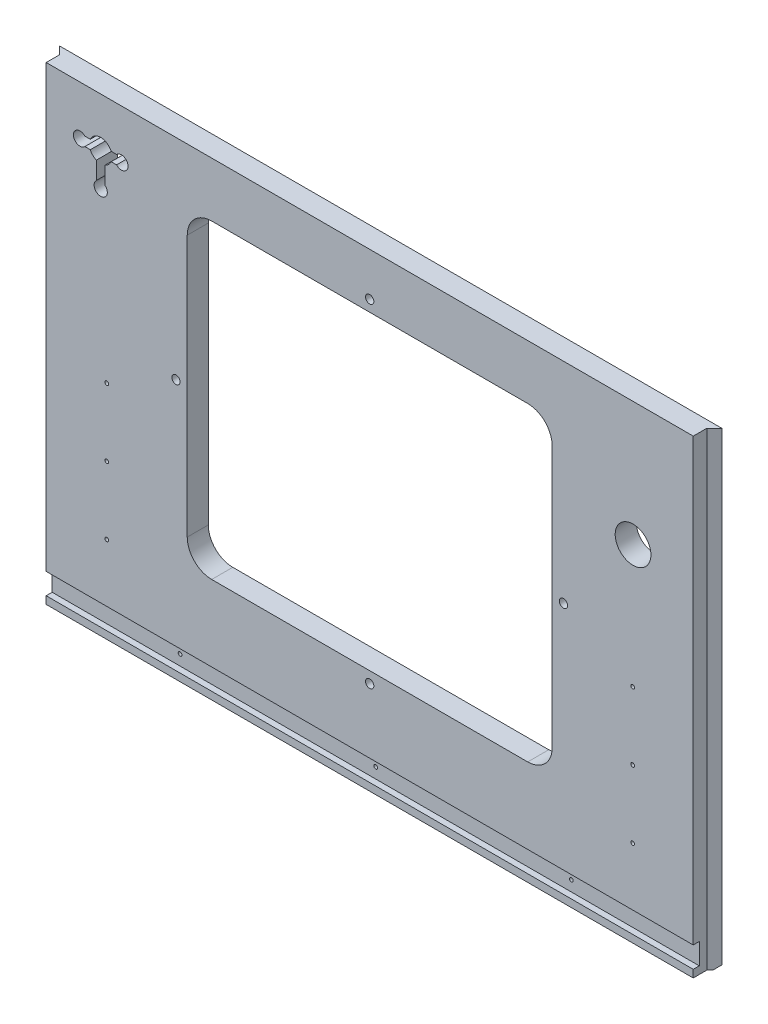
SolidWorks part; units mm, degrees
material "Pine"
ref_plane "Front Plane" through (0, 0, 0) normal (0, 0, 1) x (1, 0, 0)
ref_plane "Top Plane" through (0, 0, 0) normal (0, 1, 0) x (1, 0, 0)
ref_plane "Right Plane" through (0, 0, 0) normal (1, 0, 0) x (0, 0, -1)
sketch "Sketch1" plane through (0, 0, 0) normal (0, 0, 1) x (1, 0, 0)
  line L0 (8932.6508, -5243.5125) -> (10226.1458, -5243.5125)
  line L1 (9086.3208, -4722.0918) -> (10222.9708, -4853.7812)
  line L2 (8914.8708, -6342.0625) -> (10197.5708, -6342.0625)
  line L3 (8914.8708, -5808.6625) -> (10197.5708, -5808.6625)
  line L4 (8919.6333, -5253.0375) -> (10218.2083, -5253.0375)
  line L5 (9134.2633, -4656.1375) -> (9134.2633, -4638.3575)
  line L6 (9091.0833, -4638.3575) -> (9134.2633, -4638.3575)
  line L7 (9091.0833, -4567.2375) -> (9091.0833, -4638.3575)
  line L8 (9134.2633, -4656.1375) -> (9581.3033, -4656.1375)
  line L9 (9091.0833, -4567.2375) -> (9624.4833, -4567.2375)
  line L10 (9581.3033, -4656.1375) -> (9581.3033, -4638.3575)
  line L11 (9581.3033, -4638.3575) -> (9624.4833, -4638.3575)
  line L12 (9624.4833, -4567.2375) -> (9624.4833, -4638.3575)
  line L13 (8932.6508, -5225.7325) -> (9344.9775, -5225.7325)
  line L14 (8932.6508, -5256.2125) -> (8932.6508, -5243.5125)
  line L15 (8911.6958, -5256.2125) -> (8932.6508, -5256.2125)
  line L16 (8914.8708, -4722.0918) -> (9086.3208, -4722.0918)
  line L17 (8911.6958, -4715.5913) -> (8932.6508, -4715.5913)
  line L18 (8914.8708, -6342.0625) -> (8914.8708, -5808.6625)
  line L19 (12082.9917, -4722.0918) -> (10946.3417, -4853.7812)
  line L20 (12236.6617, -5243.5125) -> (10943.1667, -5243.5125)
  line L21 (10951.1042, -5253.0375) -> (12249.6792, -5253.0375)
  line L22 (10838.3917, -5656.2625) -> (11308.2917, -5656.2625)
  line L23 (10838.3917, -5719.7625) -> (11308.2917, -5719.7625)
  line L24 (10838.3917, -5742.5368) -> (11308.2917, -5742.5368)
  line L25 (10806.6417, -6342.0625) -> (11340.0417, -6342.0625)
  line L26 (10803.4667, -6335.7125) -> (11343.2167, -6335.7125)
  line L27 (10803.4667, -6317.9325) -> (11343.2167, -6317.9325)
  line L28 (10943.1667, -5225.7325) -> (11376.4483, -5225.7325)
  line L29 (11506.7292, -4754.5625) -> (10806.6417, -4827.5875)
  line L30 (11506.7292, -4567.2375) -> (11506.7292, -4754.5625)
  line L31 (10806.6417, -4567.2375) -> (10806.6417, -4827.5875)
  line L32 (10806.6417, -4567.2375) -> (11506.7292, -4567.2375)
  line L33 (10235.6708, -6329.3625) -> (10245.1958, -6329.3625)
  line L34 (10245.1958, -6329.3625) -> (10254.7208, -6278.5625)
  line L35 (10302.3458, -6329.3625) -> (10311.8708, -6278.5625)
  line L36 (10302.3458, -6329.3625) -> (10292.8208, -6329.3625)
  line L37 (10245.1958, -5821.3625) -> (10254.7208, -5872.1625)
  line L38 (10235.6708, -5821.3625) -> (10245.1958, -5821.3625)
  line L39 (10292.8208, -5821.3625) -> (10302.3458, -5821.3625)
  line L40 (10302.3458, -5821.3625) -> (10311.8708, -5872.1625)
  line L41 (10235.6708, -5821.3625) -> (10235.6708, -6329.3625)
  line L42 (10254.7208, -5872.1625) -> (10254.7208, -6278.5625)
  line L43 (10311.8708, -5872.1625) -> (10311.8708, -6278.5625)
  line L44 (10292.8208, -5821.3625) -> (10292.8208, -6329.3625)
  line L45 (8932.6508, -5225.7325) -> (8932.6508, -4715.5913)
  line L46 (8911.6958, -4715.5913) -> (8911.6958, -5256.2125)
  line L47 (8914.8708, -5248.275) -> (8914.8708, -4722.0918)
  line L48 (8919.6333, -5253.0375) -> (8914.8708, -5248.275)
  line L49 (8914.8708, -5145.0875) -> (8937.426, -5145.0875)
  line L50 (8914.8708, -5202.2375) -> (8937.426, -5202.2375)
  line L51 (10838.3917, -5656.2625) -> (10838.3917, -5719.7625)
  line L52 (10832.0417, -5736.1868) -> (10856.1717, -5736.1868)
  line L53 (10806.6417, -6342.0625) -> (10806.6417, -5818.7368)
  line L54 (10832.0417, -5649.9125) -> (10856.1717, -5649.9125)
  line L55 (10832.0417, -5726.1125) -> (10856.1717, -5726.1125)
  line L56 (10806.6417, -5818.7368) -> (10833.9015, -5818.7368)
  line L57 (10832.0417, -5806.0442) -> (10851.6815, -5806.0442)
  line L58 (10856.1717, -5801.5541) -> (10856.1717, -5736.1868)
  line L59 (10838.3917, -5814.2467) -> (10838.3917, -5742.5368)
  line L60 (10832.0417, -5806.0442) -> (10832.0417, -5736.1868)
  line L61 (10803.4667, -6317.9325) -> (10803.4667, -6335.7125)
  line L62 (10197.5708, -5808.6625) -> (10197.5708, -6342.0625)
  line L63 (9762.3842, -6348.4125) -> (9762.3842, -5802.3125)
  line L64 (9780.1642, -6348.4125) -> (9762.3842, -6348.4125)
  line L65 (9780.1642, -5802.3125) -> (9780.1642, -6348.4125)
  line L66 (9762.3842, -5802.3125) -> (9780.1642, -5802.3125)
  line L67 (9332.2775, -6348.4125) -> (9332.2775, -5802.3125)
  line L68 (9332.2775, -6348.4125) -> (9350.0575, -6348.4125)
  line L69 (9350.0575, -5802.3125) -> (9350.0575, -6348.4125)
  line L70 (9332.2775, -5802.3125) -> (9350.0575, -5802.3125)
  line L71 (9993.8374, -6061.075) -> (9993.8374, -6045.2418)
  line L72 (9998.5999, -6065.8375) -> (10014.4331, -6065.8375)
  line L73 (9998.5999, -6084.8875) -> (10014.4331, -6084.8875)
  line L74 (9993.8374, -6105.4832) -> (9993.8374, -6089.65)
  line L75 (9974.7874, -6105.4832) -> (9974.7874, -6089.65)
  line L76 (9954.1917, -6084.8875) -> (9970.0249, -6084.8875)
  line L77 (9974.7874, -6061.075) -> (9974.7874, -6045.2418)
  line L78 (9954.1917, -6065.8375) -> (9970.0249, -6065.8375)
  line L79 (10793.9417, -6237.2875) -> (10816.4969, -6237.2875)
  line L80 (10793.9417, -6294.4375) -> (10816.4969, -6294.4375)
  line L81 (10856.1717, -5649.9125) -> (10856.1717, -5726.1125)
  line L82 (10832.0417, -5726.1125) -> (10832.0417, -5649.9125)
  line L83 (10226.1458, -5225.7325) -> (10226.1458, -5243.5125)
  line L84 (10205.1908, -5257.8) -> (10205.1908, -4844.2499)
  line L85 (10230.9083, -4844.2499) -> (10230.9083, -5257.8)
  line L86 (10205.1908, -5257.8) -> (10230.9083, -5257.8)
  line L87 (10205.1908, -4844.2499) -> (10230.9083, -4844.2499)
  line L88 (10946.3417, -5176.8375) -> (10968.8969, -5176.8375)
  line L89 (9349.4676, -5141.9125) -> (9358.2674, -5141.9125)
  line L90 (10946.3417, -5119.6875) -> (10968.8969, -5119.6875)
  line L91 (9929.011, -4660.9635) -> (10066.0807, -4660.9635)
  line L92 (9929.011, -4678.7435) -> (10066.0807, -4678.7435)
  line L93 (10943.1667, -5225.7325) -> (10943.1667, -5243.5125)
  line L94 (10946.3417, -5248.275) -> (10951.1042, -5253.0375)
  line L95 (10946.3417, -5257.8063) -> (10946.3417, -4849.0188)
  line L96 (10964.1217, -5257.8) -> (10964.1217, -4844.2499)
  line L97 (10938.4042, -4844.2499) -> (10938.4042, -5257.8)
  line L98 (10938.4042, -5257.8) -> (10964.1217, -5257.8)
  line L99 (10964.1217, -4844.2499) -> (10938.4042, -4844.2499)
  line L100 (10344.8908, -4560.8875) -> (10369.0208, -4560.8875)
  line L101 (10344.8908, -4560.8875) -> (10369.0208, -4560.8875)
  line L102 (10800.2917, -4560.8875) -> (10824.4217, -4560.8875)
  line L103 (10200.4156, -5119.6875) -> (10222.9708, -5119.6875)
  line L104 (10200.4156, -5176.8375) -> (10222.9708, -5176.8375)
  line L105 (9344.9775, -5146.4026) -> (9344.9775, -5225.7325)
  line L106 (10344.8908, -4560.8875) -> (10344.8908, -4833.9375)
  line L107 (9792.8642, -5225.7325) -> (9792.8642, -5146.4026)
  line L108 (9362.7575, -5225.7325) -> (9775.0842, -5225.7325)
  line L109 (9680.3633, -4761.8396) -> (9680.3633, -4559.9604)
  line L110 (9656.2333, -4559.9604) -> (9680.3633, -4559.9604)
  line L111 (9656.2333, -4761.8396) -> (9680.3633, -4761.8396)
  line L112 (9656.2333, -4761.8396) -> (9656.2333, -4559.9604)
  line L113 (9779.5743, -5141.9125) -> (9788.374, -5141.9125)
  line L114 (10070.5708, -4665.4536) -> (10070.5708, -4674.2534)
  line L115 (9924.5208, -4674.2534) -> (9924.5208, -4665.4536)
  line L116 (12127.4417, -6188.3925) -> (12205.5015, -6188.3925)
  line L117 (12209.9917, -6170.6125) -> (12209.9917, -6183.9024)
  line L118 (9792.8642, -5225.7325) -> (10226.1458, -5225.7325)
  line L119 (9662.5833, -4754.5625) -> (10362.6708, -4827.5875)
  line L120 (9662.5833, -4567.2375) -> (9662.5833, -4754.5625)
  line L121 (10362.6708, -4567.2375) -> (10362.6708, -4827.5875)
  line L122 (9662.5833, -4567.2375) -> (10362.6708, -4567.2375)
  line L123 (10824.4217, -4833.9375) -> (10800.2917, -4833.9375)
  line L124 (10800.2917, -4833.9375) -> (10800.2917, -4560.8875)
  line L125 (10824.4217, -4560.8875) -> (10824.4217, -4833.9375)
  line L126 (10344.8908, -4833.9375) -> (10369.0208, -4833.9375)
  line L127 (10369.0208, -4833.9375) -> (10369.0208, -4560.8875)
  line L128 (10222.9708, -5248.275) -> (10218.2083, -5253.0375)
  line L129 (10222.9708, -5257.8063) -> (10222.9708, -4849.0188)
  line L130 (11734.6544, -5701.375) -> (11739.2301, -5701.375)
  line L131 (9362.7575, -5225.7325) -> (9362.7575, -5146.4026)
  line L132 (9775.0842, -5146.4026) -> (9775.0842, -5225.7325)
  line L133 (11761.3864, -5701.375) -> (11756.8282, -5701.375)
  line L134 (11734.6544, -5693.755) -> (11739.2301, -5693.755)
  line L135 (11761.4039, -5693.755) -> (11756.8282, -5693.755)
  line L136 (11734.6544, -5701.375) -> (11739.2301, -5701.375)
  line L137 (11744.3462, -5721.3024) -> (11744.3462, -5706.4179)
  line L138 (11751.7122, -5721.3024) -> (11751.7122, -5706.4179)
  line L139 (11740.0917, -6170.6125) -> (11740.0917, -6183.9024)
  line L140 (11689.2917, -6188.3925) -> (11822.6417, -6188.3925)
  line L141 (11689.2917, -6348.4093) -> (11689.2917, -6164.2657)
  line L142 (11689.2917, -6164.2657) -> (11746.4417, -6164.2657)
  line L143 (11746.4417, -6164.2657) -> (11746.4417, -6188.3925)
  line L144 (11689.2917, -6164.2657) -> (11746.4417, -6164.2657)
  line L145 (11340.0417, -5818.7368) -> (11340.0417, -6342.0625)
  line L146 (11290.5117, -5726.1125) -> (11314.6417, -5726.1125)
  line L147 (11290.5117, -5649.9125) -> (11290.5117, -5726.1125)
  line L148 (11340.0417, -5818.7368) -> (11312.7818, -5818.7368)
  line L149 (11314.6417, -5806.0442) -> (11295.0018, -5806.0442)
  line L150 (11290.5117, -5801.5541) -> (11290.5117, -5736.1868)
  line L151 (11308.2917, -5814.2467) -> (11308.2917, -5742.5368)
  line L152 (11314.6417, -5806.0442) -> (11314.6417, -5736.1868)
  line L153 (11290.5117, -5736.1868) -> (11314.6417, -5736.1868)
  line L154 (11848.0417, -6267.1325) -> (11962.3417, -6267.1325)
  line L155 (11962.3417, -6267.1325) -> (11962.3417, -6203.6325)
  line L156 (11343.2167, -6317.9325) -> (11343.2167, -6335.7125)
  line L157 (11365.4417, -5656.2625) -> (11365.4417, -5719.7625)
  line L158 (11365.4417, -5656.2625) -> (11479.7417, -5656.2625)
  line L159 (11778.1917, -6071.3937) -> (11802.3217, -6071.3937)
  line L160 (11314.6417, -5726.1125) -> (11314.6417, -5649.9125)
  line L161 (11314.6417, -5649.9125) -> (11290.5117, -5649.9125)
  line L162 (11308.2917, -5719.7625) -> (11308.2917, -5656.2625)
  line L163 (11689.2917, -6348.4093) -> (11713.4217, -6348.4093)
  line L164 (12203.6417, -6164.2657) -> (12260.7917, -6164.2657)
  line L165 (11713.4217, -6348.4093) -> (11713.4217, -6164.2657)
  line L166 (11695.6417, -6342.0625) -> (11695.6417, -6170.6125)
  line L167 (11695.6417, -6048.5337) -> (11699.4517, -6052.3437)
  line L168 (11822.6417, -6292.5325) -> (11822.6417, -6188.3925)
  line L169 (11695.6417, -6342.0625) -> (11695.6417, -6170.6125)
  line L170 (11848.0417, -6203.6325) -> (11962.3417, -6203.6325)
  line L171 (11848.0417, -6203.6325) -> (11848.0417, -6267.1325)
  line L172 (11987.7417, -6267.1325) -> (11987.7417, -6203.6325)
  line L173 (11784.5417, -6077.7437) -> (11784.5417, -6141.2438)
  line L174 (11517.8417, -5656.2625) -> (11632.1417, -5656.2625)
  line L175 (11632.1417, -5656.2625) -> (11632.1417, -5719.7625)
  line L176 (11632.1417, -5719.7625) -> (11517.8417, -5719.7625)
  line L177 (11517.8417, -5719.7625) -> (11517.8417, -5656.2625)
  line L178 (11692.4667, -6028.2137) -> (11692.4667, -6045.9937)
  line L179 (11695.6417, -5979.3188) -> (11718.1969, -5979.3188)
  line L180 (11695.6417, -5922.1687) -> (11718.1969, -5922.1687)
  line L181 (11821.0415, -5722.9375) -> (11821.0415, -5943.6)
  line L182 (11687.7042, -5651.5) -> (11701.9917, -5651.5)
  line L183 (11687.7042, -5651.5) -> (11687.7042, -6055.5251)
  line L184 (11687.7042, -6055.5251) -> (11701.9917, -6055.5251)
  line L185 (11701.9917, -6055.5251) -> (11701.9917, -5651.5)
  line L186 (11695.6417, -6055.2013) -> (11695.6417, -5649.595)
  line L187 (11695.6417, -5656.2625) -> (11695.6417, -6048.5337)
  line L188 (11695.6417, -6170.6125) -> (11740.0917, -6170.6125)
  line L189 (12203.6417, -6164.2657) -> (12203.6417, -6188.3925)
  line L190 (12254.4417, -6342.0625) -> (12254.4417, -6170.6125)
  line L191 (12129.0419, -5943.6) -> (12129.0419, -5722.9375)
  line L192 (12254.4417, -6048.5337) -> (12250.6317, -6052.3437)
  line L193 (12257.6167, -6045.9937) -> (12257.6167, -6028.2137)
  line L194 (12248.0917, -5651.5) -> (12262.3792, -5651.5)
  line L195 (12262.3792, -5651.5) -> (12262.3792, -6055.5251)
  line L196 (12262.3792, -6055.5251) -> (12248.0917, -6055.5251)
  line L197 (12248.0917, -6055.5251) -> (12248.0917, -5651.5)
  line L198 (12254.4417, -6141.2438) -> (12254.4417, -6077.7437)
  line L199 (12236.6617, -6164.2657) -> (12260.7917, -6164.2657)
  line L200 (12102.0417, -6267.1325) -> (11987.7417, -6267.1325)
  line L201 (11330.1865, -6237.2875) -> (11352.7417, -6237.2875)
  line L202 (11330.1865, -6294.4375) -> (11352.7417, -6294.4375)
  line L203 (11474.6617, -5851.8425) -> (11492.4417, -5851.8425)
  line L204 (11474.6617, -5808.6625) -> (11474.6617, -5851.8425)
  line L205 (11403.5417, -5808.6625) -> (11474.6617, -5808.6625)
  line L206 (11492.4417, -5851.8425) -> (11492.4417, -6298.8825)
  line L207 (11403.5417, -6342.0625) -> (11403.5417, -5808.6625)
  line L208 (11474.6617, -6298.8825) -> (11492.4417, -6298.8825)
  line L209 (11474.6617, -6342.0625) -> (11474.6617, -6298.8825)
  line L210 (11403.5417, -6342.0625) -> (11474.6617, -6342.0625)
  line L211 (11619.4417, -5851.8425) -> (11601.6617, -5851.8425)
  line L212 (11601.6617, -5808.6625) -> (11601.6617, -5851.8425)
  line L213 (11530.5417, -5808.6625) -> (11601.6617, -5808.6625)
  line L214 (11619.4417, -5851.8425) -> (11619.4417, -6298.8825)
  line L215 (11530.5417, -6342.0625) -> (11530.5417, -5808.6625)
  line L216 (11619.4417, -6298.8825) -> (11601.6617, -6298.8825)
  line L217 (11601.6617, -6342.0625) -> (11601.6617, -6298.8825)
  line L218 (11530.5417, -6342.0625) -> (11601.6617, -6342.0625)
  line L219 (11479.7417, -5719.7625) -> (11479.7417, -5656.2625)
  line L220 (11365.4417, -5719.7625) -> (11479.7417, -5719.7625)
  line L221 (11778.1917, -6147.5937) -> (11802.3217, -6147.5937)
  line L222 (11802.3217, -6071.3937) -> (11802.3217, -6147.5937)
  line L223 (11778.1917, -6147.5937) -> (11778.1917, -6071.3937)
  line L224 (12254.4417, -5922.1687) -> (12231.8865, -5922.1687)
  line L225 (12254.4417, -5979.3188) -> (12231.8865, -5979.3188)
  line L226 (12254.4417, -6055.2013) -> (12254.4417, -5649.595)
  line L227 (12254.4417, -6048.5337) -> (12254.4417, -5656.2625)
  line L228 (11841.6917, -5702.2873) -> (12108.3917, -5702.2873)
  line L229 (11822.6417, -6292.5325) -> (12127.4417, -6292.5325)
  line L230 (12127.4417, -6292.5325) -> (12127.4417, -6188.3925)
  line L231 (12254.4417, -6170.6125) -> (12209.9917, -6170.6125)
  line L232 (11695.6417, -6342.0625) -> (12254.4417, -6342.0625)
  line L233 (12236.6617, -6348.4093) -> (12260.7917, -6348.4093)
  line L234 (12260.7917, -6348.4093) -> (12260.7917, -6164.2657)
  line L235 (12236.6617, -6348.4093) -> (12236.6617, -6164.2657)
  line L236 (12102.0417, -6203.6325) -> (12102.0417, -6267.1325)
  line L237 (11987.7417, -6203.6325) -> (12102.0417, -6203.6325)
  line L238 (12236.6617, -6147.5937) -> (12236.6617, -6071.3937)
  line L239 (12203.6417, -6188.3925) -> (12260.7917, -6188.3925)
  line L240 (11098.7417, -4665.4536) -> (11098.7417, -4674.2534)
  line L241 (11394.2283, -5146.4026) -> (11394.2283, -5225.7325)
  line L242 (11376.4483, -5225.7325) -> (11376.4483, -5146.4026)
  line L243 (11394.2283, -5225.7325) -> (11806.555, -5225.7325)
  line L244 (11841.6917, -5964.2502) -> (12108.3917, -5964.2502)
  line L245 (12236.6617, -6147.5937) -> (12260.7917, -6147.5937)
  line L246 (12236.6617, -5256.2125) -> (12236.6617, -5243.5125)
  line L247 (12260.7917, -6147.5937) -> (12260.7917, -6071.3937)
  line L248 (12260.7917, -6071.3937) -> (12236.6617, -6071.3937)
  line L249 (12254.4417, -6077.7437) -> (11784.5417, -6077.7437)
  line L250 (11784.5417, -6141.2438) -> (12254.4417, -6141.2438)
  line L252 (12254.4417, -5656.2625) -> (11695.6417, -5656.2625)
  line L253 (11699.4517, -6052.3437) -> (12250.6317, -6052.3437)
  line L254 (11692.4667, -6045.9937) -> (12257.6167, -6045.9937)
  line L255 (11692.4667, -6028.2137) -> (12257.6167, -6028.2137)
  line L256 (11824.335, -5146.4026) -> (11824.335, -5225.7325)
  line L257 (11811.0451, -5141.9125) -> (11819.8449, -5141.9125)
  line L258 (11244.7917, -4674.2534) -> (11244.7917, -4665.4536)
  line L259 (11806.555, -5225.7325) -> (11806.555, -5146.4026)
  line L260 (11488.9492, -4761.8396) -> (11488.9492, -4559.9604)
  line L261 (11488.9492, -4559.9604) -> (11513.0792, -4559.9604)
  line L262 (11488.9492, -4761.8396) -> (11513.0792, -4761.8396)
  line L263 (11513.0792, -4761.8396) -> (11513.0792, -4559.9604)
  line L264 (11240.3015, -4660.9635) -> (11103.2318, -4660.9635)
  line L265 (11103.2318, -4678.7435) -> (11240.3015, -4678.7435)
  line L266 (12236.6617, -5225.7325) -> (12236.6617, -4715.5913)
  line L267 (12257.6167, -4715.5913) -> (12257.6167, -5256.2125)
  line L268 (12254.4417, -5248.275) -> (12254.4417, -4722.0918)
  line L269 (12236.6617, -5225.7325) -> (11824.335, -5225.7325)
  line L270 (12035.0492, -4656.1375) -> (12035.0492, -4638.3575)
  line L271 (12078.2292, -4638.3575) -> (12035.0492, -4638.3575)
  line L272 (12078.2292, -4567.2375) -> (12078.2292, -4638.3575)
  line L273 (12035.0492, -4656.1375) -> (11588.0092, -4656.1375)
  line L274 (11544.8292, -4567.2375) -> (12078.2292, -4567.2375)
  line L275 (11588.0092, -4656.1375) -> (11588.0092, -4638.3575)
  line L276 (11544.8292, -4638.3575) -> (11588.0092, -4638.3575)
  line L277 (11544.8292, -4567.2375) -> (11544.8292, -4638.3575)
  line L278 (12249.6792, -5253.0375) -> (12254.4417, -5248.275)
  line L280 (12257.6167, -5256.2125) -> (12236.6617, -5256.2125)
  line L281 (12231.8865, -5145.0875) -> (12254.4417, -5145.0875)
  line L282 (12231.8865, -5202.2375) -> (12254.4417, -5202.2375)
  line L283 (12236.6617, -4715.5913) -> (12257.6167, -4715.5913)
  line L284 (12082.9917, -4722.0918) -> (12254.4417, -4722.0918)
  line L285 (11380.9385, -5141.9125) -> (11389.7382, -5141.9125)
  circle A0 centre (8923.7608, -4778.9042) radius 1.5875
  circle A1 centre (9062.6598, -4736.3765) radius 2.3685
  circle A2 centre (9051.3958, -6281.7375) radius 22.225
  circle A3 centre (9083.1458, -6249.9875) radius 1.5875
  circle A4 centre (9083.1458, -6313.4875) radius 1.5875
  circle A5 centre (9019.6458, -6249.9875) radius 1.5875
  circle A6 centre (9019.6458, -6313.4875) radius 1.5875
  circle A7 centre (8972.3383, -5202.2375) radius 1.5875
  circle A8 centre (8923.7608, -5015.9708) radius 1.5875
  circle A9 centre (8923.7608, -5134.5042) radius 1.5875
  circle A10 centre (9054.5708, -5234.6225) radius 1.5875
  circle A11 centre (8923.7608, -4897.4375) radius 1.5875
  circle A12 centre (8972.3383, -5087.9375) radius 1.5875
  circle A13 centre (8972.3383, -5145.0875) radius 1.5875
  circle A14 centre (10847.2817, -5668.9625) radius 1.5875
  circle A15 centre (10847.2817, -5707.0625) radius 1.5875
  circle A16 centre (10847.2817, -5755.2368) radius 1.5875
  circle A17 centre (10851.4092, -6237.2875) radius 1.5875
  circle A18 centre (10851.4092, -6294.4375) radius 1.5875
  circle A19 centre (10847.2817, -5793.3442) radius 1.5875
  arc A20 (10833.9015, -5818.7368) -> (10838.3917, -5814.2467) centre (10836.1466, -5816.4918) ccw
  arc A21 (10851.6815, -5806.0442) -> (10856.1717, -5801.5541) centre (10853.9266, -5803.7992) ccw
  circle A22 centre (10882.8417, -6040.4375) radius 1.5875
  circle A23 centre (10882.8417, -6218.2375) radius 1.5875
  circle A24 centre (10882.8417, -5862.6375) radius 1.5875
  circle A25 centre (10908.2417, -6326.8225) radius 1.5875
  circle A26 centre (10908.2417, -6326.8225) radius 1.5875
  circle A27 centre (10851.4092, -6180.1375) radius 1.5875
  circle A28 centre (10815.5317, -4783.4231) radius 1.5875
  circle A29 centre (10815.5317, -4696.9488) radius 1.5875
  circle A30 centre (10815.5317, -4610.4746) radius 1.5875
  circle A31 centre (10979.1323, -4867.0082) radius 2.3685
  circle A32 centre (10190.1802, -4867.0082) radius 2.3685
  circle A33 centre (10955.2317, -4929.9812) radius 1.5875
  circle A34 centre (10955.2317, -5031.5812) radius 1.5875
  circle A35 centre (10214.0808, -4929.9812) radius 1.5875
  circle A36 centre (10214.0808, -5031.5812) radius 1.5875
  circle A37 centre (9341.1675, -6265.8625) radius 1.5875
  circle A38 centre (9771.2742, -5884.8625) radius 1.5875
  circle A39 centre (9771.2742, -6138.8625) radius 1.5875
  circle A40 centre (9771.2742, -6011.8625) radius 1.5875
  arc A41 (10036.2287, -6113.8083) -> (10051.3426, -6111.6033) centre (10042.9639, -6107.0732) ccw
  arc A42 (10051.3426, -6111.6033) -> (10051.3426, -6039.1217) centre (9984.3124, -6075.3625) ccw
  arc A43 (10051.3426, -6039.1217) -> (10036.2287, -6036.9167) centre (10042.9639, -6043.6518) ccw
  arc A44 (10034.5851, -6102.5431) -> (10034.5851, -6048.1819) centre (9984.3124, -6075.3625) ccw
  arc A45 (10034.5851, -6102.5431) -> (10036.2287, -6113.8083) centre (10042.9639, -6107.0732) ccw
  arc A46 (10036.2287, -6036.9167) -> (10034.5851, -6048.1819) centre (10042.9639, -6043.6518) ccw
  arc A47 (9945.8666, -6127.2787) -> (9948.0717, -6142.3927) centre (9952.6018, -6134.0139) ccw
  arc A48 (9948.0717, -6142.3927) -> (10020.5532, -6142.3927) centre (9984.3124, -6075.3625) ccw
  arc A49 (10020.5532, -6142.3927) -> (10022.7583, -6127.2787) centre (10016.0231, -6134.0139) ccw
  arc A50 (9957.1319, -6125.6352) -> (10011.493, -6125.6352) centre (9984.3124, -6075.3625) ccw
  arc A51 (9957.1319, -6125.6352) -> (9945.8666, -6127.2787) centre (9952.6018, -6134.0139) ccw
  arc A52 (10022.7583, -6127.2787) -> (10011.493, -6125.6352) centre (10016.0231, -6134.0139) ccw
  arc A53 (9932.3962, -6036.9167) -> (9917.2822, -6039.1217) centre (9925.661, -6043.6518) ccw
  arc A54 (9917.2822, -6039.1217) -> (9917.2822, -6111.6033) centre (9984.3124, -6075.3625) ccw
  arc A55 (9917.2822, -6111.6033) -> (9932.3962, -6113.8083) centre (9925.661, -6107.0732) ccw
  arc A56 (9934.0398, -6048.1819) -> (9934.0398, -6102.5431) centre (9984.3124, -6075.3625) ccw
  arc A57 (9934.0398, -6048.1819) -> (9932.3962, -6036.9167) centre (9925.661, -6043.6518) ccw
  arc A58 (9932.3962, -6113.8083) -> (9934.0398, -6102.5431) centre (9925.661, -6107.0732) ccw
  arc A59 (9945.8666, -6023.4463) -> (9957.1319, -6025.0898) centre (9952.6018, -6016.7111) ccw
  arc A60 (10011.493, -6025.0898) -> (10022.7583, -6023.4463) centre (10016.0231, -6016.7111) ccw
  arc A61 (10011.493, -6025.0898) -> (9957.1319, -6025.0898) centre (9984.3124, -6075.3625) ccw
  arc A62 (9948.0717, -6008.3323) -> (9945.8666, -6023.4463) centre (9952.6018, -6016.7111) ccw
  arc A63 (10020.5532, -6008.3323) -> (9948.0717, -6008.3323) centre (9984.3124, -6075.3625) ccw
  arc A64 (10022.7583, -6023.4463) -> (10020.5532, -6008.3323) centre (10016.0231, -6016.7111) ccw
  arc A65 (10005.0943, -6187.7574) -> (10096.7073, -6096.1443) centre (9984.3124, -6075.3625) ccw
  arc A66 (9993.8374, -6178.3911) -> (10005.0943, -6187.7574) centre (10003.3624, -6178.3911) ccw
  arc A67 (10001.6306, -6169.0249) -> (10077.9748, -6092.6807) centre (9984.3124, -6075.3625) ccw
  arc A68 (10087.3411, -6084.8875) -> (10077.9748, -6092.6807) centre (10087.3411, -6094.4125) ccw
  arc A69 (10001.6306, -6169.0249) -> (9993.8374, -6178.3911) centre (10003.3624, -6178.3911) ccw
  arc A70 (9963.5306, -6187.7574) -> (9974.7874, -6178.3911) centre (9965.2624, -6178.3911) ccw
  arc A71 (9871.9176, -6096.1443) -> (9963.5306, -6187.7574) centre (9984.3124, -6075.3625) ccw
  arc A72 (9881.2838, -6084.8875) -> (9871.9176, -6096.1443) centre (9881.2838, -6094.4125) ccw
  arc A73 (9890.65, -6092.6807) -> (9966.9943, -6169.0249) centre (9984.3124, -6075.3625) ccw
  arc A74 (9974.7874, -6178.3911) -> (9966.9943, -6169.0249) centre (9965.2624, -6178.3911) ccw
  arc A75 (9890.65, -6092.6807) -> (9881.2838, -6084.8875) centre (9881.2838, -6094.4125) ccw
  arc A76 (9871.9176, -6054.5807) -> (9881.2838, -6065.8375) centre (9881.2838, -6056.3125) ccw
  arc A77 (9963.5306, -5962.9676) -> (9871.9176, -6054.5807) centre (9984.3124, -6075.3625) ccw
  arc A78 (9974.7874, -5972.3339) -> (9963.5306, -5962.9676) centre (9965.2624, -5972.3339) ccw
  arc A79 (9966.9943, -5981.7001) -> (9890.65, -6058.0443) centre (9984.3124, -6075.3625) ccw
  arc A80 (9881.2838, -6065.8375) -> (9890.65, -6058.0443) centre (9881.2838, -6056.3125) ccw
  arc A81 (9966.9943, -5981.7001) -> (9974.7874, -5972.3339) centre (9965.2624, -5972.3339) ccw
  arc A82 (10077.9748, -6058.0443) -> (10087.3411, -6065.8375) centre (10087.3411, -6056.3125) ccw
  arc A83 (9993.8374, -5972.3339) -> (10001.6306, -5981.7001) centre (10003.3624, -5972.3339) ccw
  arc A84 (10077.9748, -6058.0443) -> (10001.6306, -5981.7001) centre (9984.3124, -6075.3625) ccw
  arc A85 (10087.3411, -6065.8375) -> (10096.7073, -6054.5807) centre (10087.3411, -6056.3125) ccw
  arc A86 (10096.7073, -6054.5807) -> (10005.0943, -5962.9676) centre (9984.3124, -6075.3625) ccw
  arc A87 (10005.0943, -5962.9676) -> (9993.8374, -5972.3339) centre (10003.3624, -5972.3339) ccw
  arc A88 (10014.4331, -6065.8375) -> (10018.7361, -6059.0339) centre (10014.4331, -6061.075) ccw
  arc A89 (10018.7361, -6059.0339) -> (10000.641, -6040.9388) centre (9984.3124, -6075.3625) ccw
  arc A90 (10000.641, -6040.9388) -> (9993.8374, -6045.2418) centre (9998.5999, -6045.2418) ccw
  arc A91 (9993.8374, -6061.075) -> (9998.5999, -6065.8375) centre (9998.5999, -6061.075) ccw
  arc A92 (9993.8374, -6105.4832) -> (10000.641, -6109.7862) centre (9998.5999, -6105.4832) ccw
  arc A93 (10000.641, -6109.7862) -> (10018.7361, -6091.6911) centre (9984.3124, -6075.3625) ccw
  arc A94 (10018.7361, -6091.6911) -> (10014.4331, -6084.8875) centre (10014.4331, -6089.65) ccw
  arc A95 (9998.5999, -6084.8875) -> (9993.8374, -6089.65) centre (9998.5999, -6089.65) ccw
  arc A96 (9954.1917, -6084.8875) -> (9949.8888, -6091.6911) centre (9954.1917, -6089.65) ccw
  arc A97 (9949.8888, -6091.6911) -> (9967.9839, -6109.7862) centre (9984.3124, -6075.3625) ccw
  arc A98 (9967.9839, -6109.7862) -> (9974.7874, -6105.4832) centre (9970.0249, -6105.4832) ccw
  arc A99 (9974.7874, -6089.65) -> (9970.0249, -6084.8875) centre (9970.0249, -6089.65) ccw
  arc A100 (9970.0249, -6065.8375) -> (9974.7874, -6061.075) centre (9970.0249, -6061.075) ccw
  arc A101 (9949.8888, -6059.0339) -> (9954.1917, -6065.8375) centre (9954.1917, -6061.075) ccw
  arc A102 (9967.9839, -6040.9388) -> (9949.8888, -6059.0339) centre (9984.3124, -6075.3625) ccw
  arc A103 (9974.7874, -6045.2418) -> (9967.9839, -6040.9388) centre (9970.0249, -6045.2418) ccw
  arc A104 (10096.7073, -6096.1443) -> (10087.3411, -6084.8875) centre (10087.3411, -6094.4125) ccw
  circle A105 centre (9771.2742, -6265.8625) radius 1.5875
  circle A106 centre (9341.1675, -5884.8625) radius 1.5875
  circle A107 centre (9341.1675, -6138.8625) radius 1.5875
  circle A108 centre (9341.1675, -6011.8625) radius 1.5875
  circle A109 centre (11037.2315, -4887.5494) radius 15.0812
  arc A110 (9349.4676, -5141.9125) -> (9344.9775, -5146.4026) centre (9347.2226, -5144.1576) ccw
  arc A111 (9362.7575, -5146.4026) -> (9358.2674, -5141.9125) centre (9360.5124, -5144.1576) ccw
  circle A112 centre (9946.7458, -4669.8535) radius 1.5875
  arc A113 (9924.5208, -4674.2534) -> (9929.011, -4678.7435) centre (9926.7659, -4676.4984) ccw
  circle A114 centre (11003.8092, -5176.8375) radius 1.5875
  circle A115 centre (11003.8092, -5119.6875) radius 1.5875
  circle A116 centre (10353.7808, -4696.9488) radius 1.5875
  circle A117 centre (10353.7808, -4610.4746) radius 1.5875
  circle A118 centre (10353.7808, -4783.4231) radius 1.5875
  circle A119 centre (11003.8092, -5062.5375) radius 1.5875
  circle A120 centre (9353.8675, -5160.9625) radius 1.5875
  circle A121 centre (9638.7708, -5234.6225) radius 1.5875
  circle A122 centre (9671.4733, -4724.1144) radius 1.5875
  circle A123 centre (9671.4733, -4661.3637) radius 1.5875
  circle A124 centre (9671.4733, -4598.6129) radius 1.5875
  arc A125 (9792.8642, -5146.4026) -> (9788.374, -5141.9125) centre (9790.6191, -5144.1576) ccw
  arc A126 (9779.5743, -5141.9125) -> (9775.0842, -5146.4026) centre (9777.3292, -5144.1576) ccw
  circle A127 centre (10048.3458, -4669.8535) radius 1.5875
  arc A128 (10070.5708, -4665.4536) -> (10066.0807, -4660.9635) centre (10068.3258, -4663.2086) ccw
  arc A129 (10066.0807, -4678.7435) -> (10070.5708, -4674.2534) centre (10068.3258, -4676.4984) ccw
  circle A130 centre (9997.5458, -4669.8535) radius 1.5875
  arc A131 (9929.011, -4660.9635) -> (9924.5208, -4665.4536) centre (9926.7659, -4663.2086) ccw
  circle A132 centre (10132.081, -4887.5494) radius 15.0812
  circle A133 centre (10165.5033, -5176.8375) radius 1.5875
  circle A134 centre (10165.5033, -5119.6875) radius 1.5875
  circle A135 centre (9486.3708, -5234.6225) radius 1.5875
  circle A136 centre (10165.5033, -5062.5375) radius 1.5875
  circle A137 centre (9206.9708, -5234.6225) radius 1.5875
  circle A138 centre (10070.5708, -5234.6225) radius 1.5875
  circle A139 centre (9918.1708, -5234.6225) radius 1.5875
  circle A140 centre (9783.9742, -5160.9625) radius 1.5875
  circle A141 centre (9783.9742, -5193.9825) radius 1.5875
  circle A142 centre (9353.8675, -5193.9825) radius 1.5875
  circle A143 centre (11073.3417, -6326.8225) radius 1.5875
  circle A144 centre (11073.3417, -6326.8225) radius 1.5875
  circle A145 centre (11295.2742, -6180.1375) radius 1.5875
  circle A146 centre (11295.2742, -6294.4375) radius 1.5875
  circle A147 centre (11295.2742, -6237.2875) radius 1.5875
  circle A148 centre (11975.0417, -5692.775) radius 3.4925
  circle A149 centre (11263.8417, -5862.6375) radius 1.5875
  arc A150 (11739.2301, -5701.375) -> (11744.3462, -5706.4179) centre (11748.0292, -5697.565) ccw
  arc A151 (11751.7122, -5706.4179) -> (11756.8282, -5701.375) centre (11748.0292, -5697.565) ccw
  arc A152 (11744.3462, -5721.3024) -> (11751.7122, -5721.3024) centre (11748.0292, -5725.505) ccw
  arc A153 (11734.6544, -5693.755) -> (11724.9787, -5697.565) centre (11730.5667, -5697.565) ccw
  arc A154 (11756.8282, -5693.755) -> (11739.2301, -5693.755) centre (11748.0292, -5697.565) ccw
  arc A155 (11724.9787, -5697.565) -> (11734.6544, -5701.375) centre (11730.5667, -5697.565) ccw
  arc A156 (11761.3864, -5701.375) -> (11771.0797, -5697.565) centre (11765.4842, -5697.565) ccw
  arc A157 (11771.0797, -5697.565) -> (11761.4039, -5693.755) centre (11765.4917, -5697.565) ccw
  arc A158 (11740.0917, -6183.9024) -> (11744.5818, -6188.3925) centre (11742.3367, -6186.1474) ccw
  arc A159 (12205.5015, -6188.3925) -> (12209.9917, -6183.9024) centre (12207.7466, -6186.1474) ccw
  circle A160 centre (11299.4017, -5793.3442) radius 1.5875
  arc A161 (11308.2917, -5814.2467) -> (11312.7818, -5818.7368) centre (11310.5367, -5816.4918) ccw
  arc A162 (11290.5117, -5801.5541) -> (11295.0018, -5806.0442) centre (11292.7567, -5803.7992) ccw
  circle A163 centre (11704.5317, -6314.149) radius 1.5875
  circle A164 centre (11748.9817, -6208.7125) radius 1.5875
  circle A165 centre (11263.8417, -6218.2375) radius 1.5875
  circle A166 centre (11263.8417, -6040.4375) radius 1.5875
  circle A167 centre (11238.4417, -6326.8225) radius 1.5875
  circle A168 centre (11238.4417, -6326.8225) radius 1.5875
  circle A169 centre (11299.4017, -5668.9625) radius 1.5875
  circle A170 centre (11299.4017, -5707.0625) radius 1.5875
  circle A171 centre (11726.7567, -6179.5025) radius 1.5875
  circle A172 centre (11704.5317, -6199.3198) radius 1.5875
  circle A173 centre (11748.9817, -6272.2125) radius 1.5875
  circle A174 centre (11704.5317, -6256.7344) radius 1.5875
  circle A175 centre (11299.4017, -5755.2368) radius 1.5875
  circle A176 centre (11913.4467, -6301.4225) radius 1.5875
  circle A177 centre (11790.2567, -6301.4225) radius 1.5875
  circle A178 centre (11793.4317, -6128.5437) radius 1.5875
  circle A179 centre (11753.1092, -5865.0188) radius 1.5875
  circle A180 centre (11809.9417, -6037.1038) radius 1.5875
  circle A181 centre (11809.9417, -6037.1038) radius 1.5875
  circle A182 centre (11753.1092, -5922.1687) radius 1.5875
  circle A183 centre (11975.0417, -5973.7625) radius 3.4925
  circle A184 centre (11975.0417, -6037.1038) radius 1.5875
  circle A185 centre (11753.1092, -5979.3188) radius 1.5875
  circle A186 centre (11975.0417, -6037.1038) radius 1.5875
  arc A187 (11841.6917, -5702.2873) -> (11821.0415, -5722.9375) centre (11841.6917, -5722.9375) ccw
  circle A188 centre (11811.5292, -5833.2687) radius 3.4925
  arc A189 (11821.0415, -5943.6) -> (11841.6917, -5964.2502) centre (11841.6917, -5943.6) ccw
  circle A190 centre (12196.9742, -5865.0188) radius 1.5875
  arc A191 (12129.0419, -5722.9375) -> (12108.3917, -5702.2873) centre (12108.3917, -5722.9375) ccw
  circle A192 centre (12036.6367, -6301.4225) radius 1.5875
  circle A193 centre (12159.8267, -6301.4225) radius 1.5875
  circle A194 centre (12138.5542, -5833.2687) radius 3.4925
  circle A195 centre (12197.2917, -5761.0375) radius 15.0812
  circle A196 centre (11793.4317, -6090.4437) radius 1.5875
  circle A197 centre (12196.9742, -5922.1687) radius 1.5875
  arc A198 (12108.3917, -5964.2502) -> (12129.0419, -5943.6) centre (12108.3917, -5943.6) ccw
  circle A199 centre (12196.9742, -5979.3188) radius 1.5875
  circle A200 centre (12201.1017, -6272.2125) radius 1.5875
  circle A201 centre (12245.5517, -6314.149) radius 1.5875
  circle A202 centre (12245.5517, -6256.7344) radius 1.5875
  circle A203 centre (12201.1017, -6208.7125) radius 1.5875
  circle A204 centre (12223.3267, -6179.5025) radius 1.5875
  circle A205 centre (12245.5517, -6199.3198) radius 1.5875
  circle A206 centre (11171.7667, -4669.8535) radius 1.5875
  circle A207 centre (11222.5667, -4669.8535) radius 1.5875
  arc A208 (11240.3015, -4678.7435) -> (11244.7917, -4674.2534) centre (11242.5466, -4676.4984) ccw
  circle A209 centre (11385.3383, -5193.9825) radius 1.5875
  circle A210 centre (12106.6527, -4736.3765) radius 2.3685
  circle A211 centre (12140.1417, -6037.1038) radius 1.5875
  circle A212 centre (12140.1417, -6037.1038) radius 1.5875
  circle A213 centre (12245.5517, -6090.4437) radius 1.5875
  circle A214 centre (12245.5517, -6128.5437) radius 1.5875
  circle A215 centre (11385.3383, -5160.9625) radius 1.5875
  arc A216 (11824.335, -5146.4026) -> (11819.8449, -5141.9125) centre (11822.0899, -5144.1576) ccw
  arc A217 (11811.0451, -5141.9125) -> (11806.555, -5146.4026) centre (11808.8001, -5144.1576) ccw
  circle A218 centre (11815.445, -5193.9825) radius 1.5875
  circle A219 centre (11815.445, -5160.9625) radius 1.5875
  circle A220 centre (11530.5417, -5234.6225) radius 1.5875
  circle A221 centre (11962.3417, -5234.6225) radius 1.5875
  arc A222 (11244.7917, -4665.4536) -> (11240.3015, -4660.9635) centre (11242.5466, -4663.2086) ccw
  circle A223 centre (11682.9417, -5234.6225) radius 1.5875
  circle A224 centre (11497.8392, -4724.1144) radius 1.5875
  circle A225 centre (11497.8392, -4661.3637) radius 1.5875
  circle A226 centre (11497.8392, -4598.6129) radius 1.5875
  circle A227 centre (11120.9667, -4669.8535) radius 1.5875
  arc A228 (11103.2318, -4660.9635) -> (11098.7417, -4665.4536) centre (11100.9867, -4663.2086) ccw
  arc A229 (11098.7417, -4674.2534) -> (11103.2318, -4678.7435) centre (11100.9867, -4676.4984) ccw
  circle A230 centre (12196.9742, -5202.2375) radius 1.5875
  circle A231 centre (12245.5517, -5015.9708) radius 1.5875
  circle A232 centre (12245.5517, -5134.5042) radius 1.5875
  circle A233 centre (12114.7417, -5234.6225) radius 1.5875
  circle A234 centre (12245.5517, -4897.4375) radius 1.5875
  circle A235 centre (12245.5517, -4778.9042) radius 1.5875
  circle A236 centre (12196.9742, -5087.9375) radius 1.5875
  circle A237 centre (12196.9742, -5145.0875) radius 1.5875
  circle A238 centre (11098.7417, -5234.6225) radius 1.5875
  circle A239 centre (11251.1417, -5234.6225) radius 1.5875
  arc A240 (11380.9385, -5141.9125) -> (11376.4483, -5146.4026) centre (11378.6934, -5144.1576) ccw
  arc A241 (11394.2283, -5146.4026) -> (11389.7382, -5141.9125) centre (11391.9833, -5144.1576) ccw
sketch "Sketch2" plane through (0, 0, 0) normal (0, 0, 1) x (1, 0, 0)
  line L0 (11695.6417, -6048.5337) -> (11699.4517, -6052.3437)
  line L1 (11699.4517, -6052.3437) -> (12250.6317, -6052.3437)
  line L2 (12250.6317, -6052.3437) -> (12254.4417, -6048.5337)
  line L3 (12254.4417, -6048.5337) -> (12254.4417, -5656.2625)
  line L4 (12254.4417, -5656.2625) -> (11695.6417, -5656.2625)
  line L5 (11695.6417, -5656.2625) -> (11695.6417, -6048.5337)
extrude "Extrude1" add sketch "Sketch2" against normal blind 17.78
sketch "Sketch3" plane through (0, 0, 0) normal (0, 0, 1) x (1, 0, 0)
  line L0 (11841.6917, -5702.2873) -> (12108.3917, -5702.2873)
  line L1 (12129.0419, -5722.9375) -> (12129.0419, -5943.6)
  line L2 (12108.3917, -5964.2502) -> (11841.6917, -5964.2502)
  line L3 (11821.0415, -5943.6) -> (11821.0415, -5722.9375)
  line L4 (11734.6544, -5693.755) -> (11739.2301, -5693.755)
  line L5 (11734.6544, -5701.375) -> (11739.2301, -5701.375)
  line L6 (11744.3462, -5706.4179) -> (11744.3462, -5721.3024)
  line L7 (11751.7122, -5706.4179) -> (11751.7122, -5721.3024)
  line L8 (11756.8282, -5701.375) -> (11761.3864, -5701.375)
  line L9 (11761.3864, -5693.755) -> (11756.8282, -5693.755)
  arc A0 (12108.3917, -5702.2873) -> (12129.0419, -5722.9375) centre (12108.3917, -5722.9375) cw
  arc A1 (12129.0419, -5943.6) -> (12108.3917, -5964.2502) centre (12108.3917, -5943.6) cw
  arc A2 (11841.6917, -5964.2502) -> (11821.0415, -5943.6) centre (11841.6917, -5943.6) cw
  arc A3 (11821.0415, -5722.9375) -> (11841.6917, -5702.2873) centre (11841.6917, -5722.9375) cw
  arc A4 (11734.6544, -5693.755) -> (11734.6544, -5701.375) centre (11730.5667, -5697.565) ccw
  arc A5 (11724.9787, -5697.565) -> (11734.6544, -5701.375) centre (11730.5667, -5697.565) ccw construction
  arc A6 (11739.2301, -5693.755) -> (11756.8282, -5693.755) centre (11748.0292, -5697.565) cw
  arc A7 (11756.8282, -5693.755) -> (11739.2301, -5693.755) centre (11748.0292, -5697.565) ccw construction
  arc A8 (11744.3462, -5721.3024) -> (11751.7122, -5721.3024) centre (11748.0292, -5725.505) ccw
  arc A9 (11744.3462, -5721.3024) -> (11751.7122, -5721.3024) centre (11748.0292, -5725.505) ccw construction
  arc A10 (11739.2301, -5701.375) -> (11744.3462, -5706.4179) centre (11748.0292, -5697.565) ccw
  arc A11 (11739.2301, -5701.375) -> (11744.3462, -5706.4179) centre (11748.0292, -5697.565) ccw construction
  arc A12 (11751.7122, -5706.4179) -> (11756.8282, -5701.375) centre (11748.0292, -5697.565) ccw
  arc A13 (11751.7122, -5706.4179) -> (11756.8282, -5701.375) centre (11748.0292, -5697.565) ccw construction
  arc A14 (11761.3864, -5701.375) -> (11771.0797, -5697.565) centre (11765.4842, -5697.565) ccw
  arc A16 (11761.3864, -5701.375) -> (11771.0797, -5697.565) centre (11765.4842, -5697.565) ccw construction
  arc A17 (11771.0797, -5697.565) -> (11761.3864, -5693.755) centre (11765.4842, -5697.565) ccw
  circle A18 centre (12197.2917, -5761.0375) radius 15.0812
  circle A19 centre (12138.5542, -5833.2687) radius 3.4925
  circle A20 centre (12196.9742, -5865.0188) radius 1.5875
  circle A21 centre (12196.9742, -5922.1687) radius 1.5875
  circle A22 centre (12196.9742, -5979.3188) radius 1.5875
  circle A23 centre (12140.1417, -6037.1038) radius 1.5875
  circle A24 centre (11975.0417, -6037.1038) radius 1.5875
  circle A25 centre (11809.9417, -6037.1038) radius 1.5875
  circle A26 centre (11753.1092, -5979.3188) radius 1.5875
  circle A27 centre (11753.1092, -5922.1687) radius 1.5875
  circle A28 centre (11753.1092, -5865.0188) radius 1.5875
  circle A29 centre (11811.5292, -5833.2687) radius 3.4925
  circle A30 centre (11975.0417, -5973.7625) radius 3.4925
  circle A31 centre (11975.0417, -5692.775) radius 3.4925
extrude "Cut-Extrude1" cut sketch "Sketch3" against normal up to surface (17.78 mm away) up to face at (11975.0417, -5919.0467, -17.78)
sketch "Sketch4" plane through (0, 0, 0) normal (0, 0, 1) x (1, 0, 0)
  line L0 (11975.0417, -6028.2137) -> (11695.6417, -6028.2137)
  line L1 (11975.0417, -6028.2137) -> (11975.0417, -6052.3437) construction
  line L2 (11695.6417, -6055.2013) -> (11695.6417, -5649.595) construction
  line L3 (11692.4667, -6028.2137) -> (12257.6167, -6028.2137) construction
  line L4 (11699.4517, -6052.3437) -> (12250.6317, -6052.3437) construction
  line L5 (11695.6417, -6028.2137) -> (11695.6417, -6045.9937)
  line L6 (11695.6417, -6045.9937) -> (12254.4417, -6045.9937)
  line L7 (12254.4417, -6055.2013) -> (12254.4417, -5649.595) construction
  line L9 (12254.4417, -6045.9937) -> (12254.4417, -6028.2137)
  line L10 (12254.4417, -6028.2137) -> (11975.0417, -6028.2137)
  dimension "D1" = 17.78
extrude "Cut-Extrude2" cut sketch "Sketch4" against normal blind 5.08
sketch "Sketch5" plane through (0, 0, 0) normal (0, 0, 1) x (1, 0, 0)
  line L0 (11687.7042, -5651.5) -> (11701.9917, -5651.5)
  line L1 (11701.9917, -5651.5) -> (11701.9917, -6055.5251)
  line L2 (11701.9917, -6055.5251) -> (11687.7042, -6055.5251)
  line L3 (11687.7042, -6055.5251) -> (11687.7042, -5651.5)
  line L4 (12248.0917, -5651.5) -> (12262.3792, -5651.5)
  line L5 (12262.3792, -5651.5) -> (12262.3792, -6055.5251)
  line L6 (12262.3792, -6055.5251) -> (12248.0917, -6055.5251)
  line L7 (12248.0917, -6055.5251) -> (12248.0917, -5651.5)
extrude "Cut-Extrude3" cut sketch "Sketch5" against normal blind 11.43
sketch "Sketch7" plane through (0, -6052.3437, 0) normal (0, -1, 0) x (1, 0, 0)
  line L0 (12248.0917, -11.43) -> (12248.0917, -17.78) construction
  line L1 (11699.4517, -17.78) -> (12250.6317, -17.78) construction
  line L2 (12248.0917, -17.78) -> (12254.4417, -17.78) construction
  line L3 (12254.4417, -17.78) -> (12254.4417, -11.43)
  line L4 (12254.4417, -11.43) -> (12248.0917, -11.43)
  line L5 (12248.0917, -11.43) -> (12254.4417, -17.78)
  line L6 (11701.9917, -11.43) -> (11701.9917, -17.78) construction
  line L7 (11701.9917, -17.78) -> (11695.6417, -17.78) construction
  line L8 (11695.6417, -17.78) -> (11695.6417, -11.43)
  line L9 (11695.6417, -11.43) -> (11701.9917, -11.43)
  line L10 (11695.6417, -17.78) -> (11701.9917, -11.43)
extrude "Cut-Extrude4" cut sketch "Sketch7" against normal up to surface (396.0813 mm away) up to face at (11975.0417, -5656.2625, -10.16)
